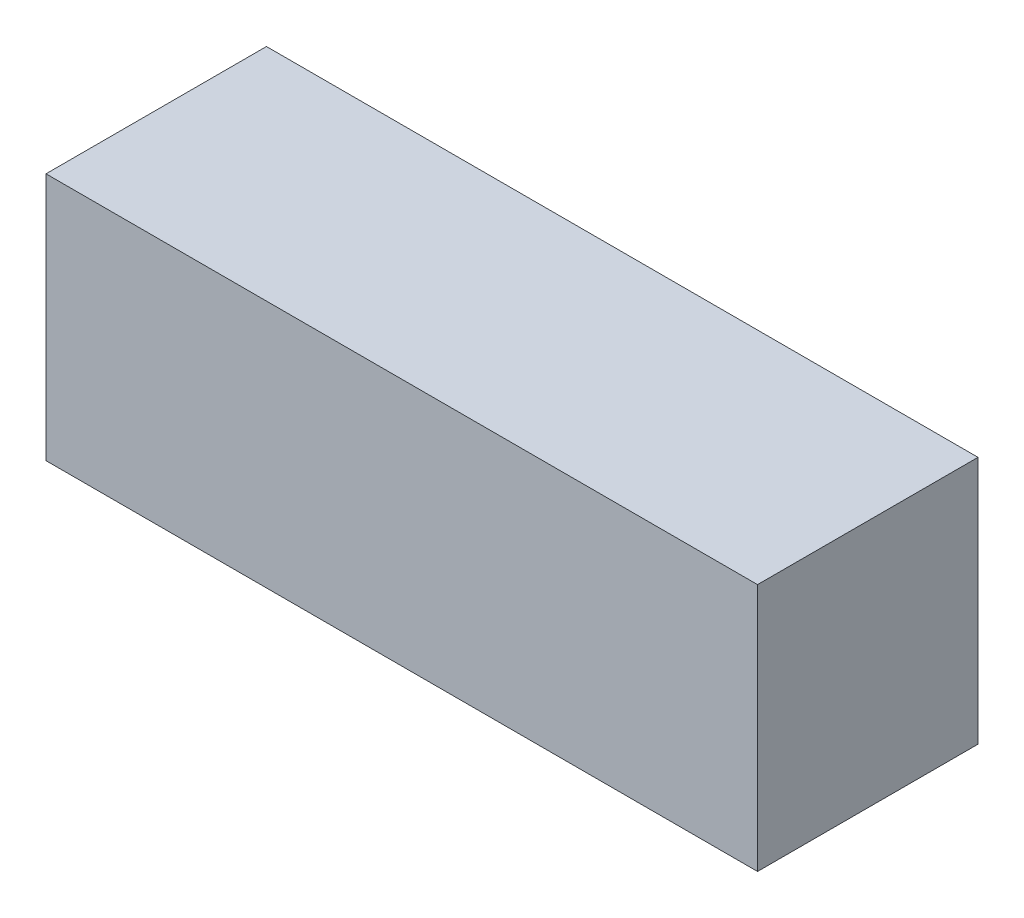
SolidWorks part; units mm, degrees
ref_plane "Front Plane" through (0, 0, 0) normal (0, 0, 1) x (1, 0, 0)
ref_plane "Top Plane" through (0, 0, 0) normal (0, 1, 0) x (1, 0, 0)
ref_plane "Right Plane" through (0, 0, 0) normal (1, 0, 0) x (0, 0, -1)
sketch "Sketch2" plane through (0, 0, 0) normal (0, 1, 0) x (1, 0, 0)
  line L1 (0, 0) -> (154.94, 0)
  line L2 (0, 0) -> (0, 48.006)
  line L3 (0, 48.006) -> (154.94, 48.006)
  line L4 (154.94, 0) -> (154.94, 48.006)
  dimension "D1" = 154.94
  dimension "D2" = 48.006
extrude "Boss-Extrude1" add sketch "Sketch2" along normal blind 54.102
equation "\"2.13.in\"=0"
